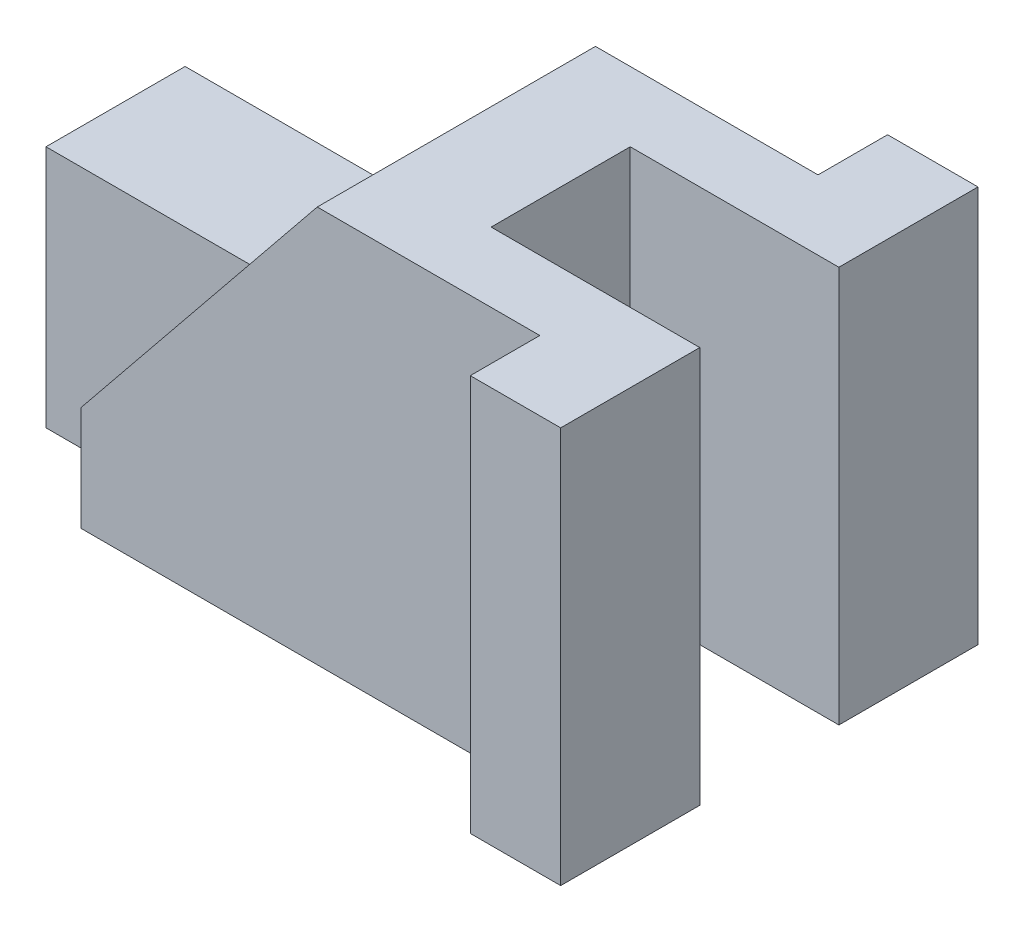
SolidWorks part; units mm, degrees
ref_plane "Front Plane" through (0, 0, 0) normal (0, 0, 1) x (1, 0, 0)
ref_plane "Top Plane" through (0, 0, 0) normal (0, 1, 0) x (1, 0, 0)
ref_plane "Right Plane" through (0, 0, 0) normal (1, 0, 0) x (0, 0, -1)
sketch "Sketch1" plane through (0, 0, 0) normal (0, 0, 1) x (1, 0, 0)
  line L0 (0, 0) -> (66, 0)
  line L1 (66, 0) -> (66, 57)
  line L2 (66, 57) -> (34, 57)
  line L3 (34, 57) -> (0, 15)
  line L4 (0, 15) -> (0, 0)
  dimension "D1" = 15
  dimension "D2" = 66
  dimension "D3" = 32
  dimension "D4" = 57
extrude "Boss-Extrude1" add sketch "Sketch1" along normal mid plane 40
sketch "Sketch2" plane through (0, 0, 0) normal (0, 0, 1) x (1, 0, 0)
  line L0 (66, 57) -> (34, 57) construction
  line L1 (66, 0) -> (79, 0)
  line L2 (66, 0) -> (66, 57)
  line L3 (66, 57) -> (79, 57)
  line L4 (79, 0) -> (79, 57)
  dimension "D1" = 13
extrude "Boss-Extrude2" add sketch "Sketch2" along normal mid plane 60
sketch "Sketch3" plane through (0, 0, 0) normal (0, 1, 0) x (1, 0, 0)
  line L0 (79, -30) -> (79, 30) construction
  line L1 (79, 10) -> (49, 10)
  line L2 (79, 10) -> (79, -10)
  line L3 (79, -10) -> (49, -10)
  line L4 (49, 10) -> (49, -10)
  line L5 (79, 30) -> (66, 30) construction
  point P8 (72.5, 30)
  dimension "D1" = 20
  dimension "D2" = 20
  dimension "D3" = 30
extrude "Cut-Extrude1" cut sketch "Sketch3" along normal through all
sketch "Sketch5" plane through (0, 0, 0) normal (1, 0, 0) x (0, 0, -1)
  line L1 (-10, 0) -> (10, 0)
  line L2 (-10, 0) -> (-10, 35)
  line L3 (-10, 35) -> (10, 35)
  line L4 (10, 0) -> (10, 35)
  line L5 (-10, 0) -> (10, 35) construction
  line L6 (-10, 35) -> (10, 0) construction
  point P0 (0, 17.5)
  dimension "D1" = 35
  dimension "D2" = 20
extrude "Boss-Extrude3" add sketch "Sketch5" along normal up to next from offset 15 offset against normal yes
